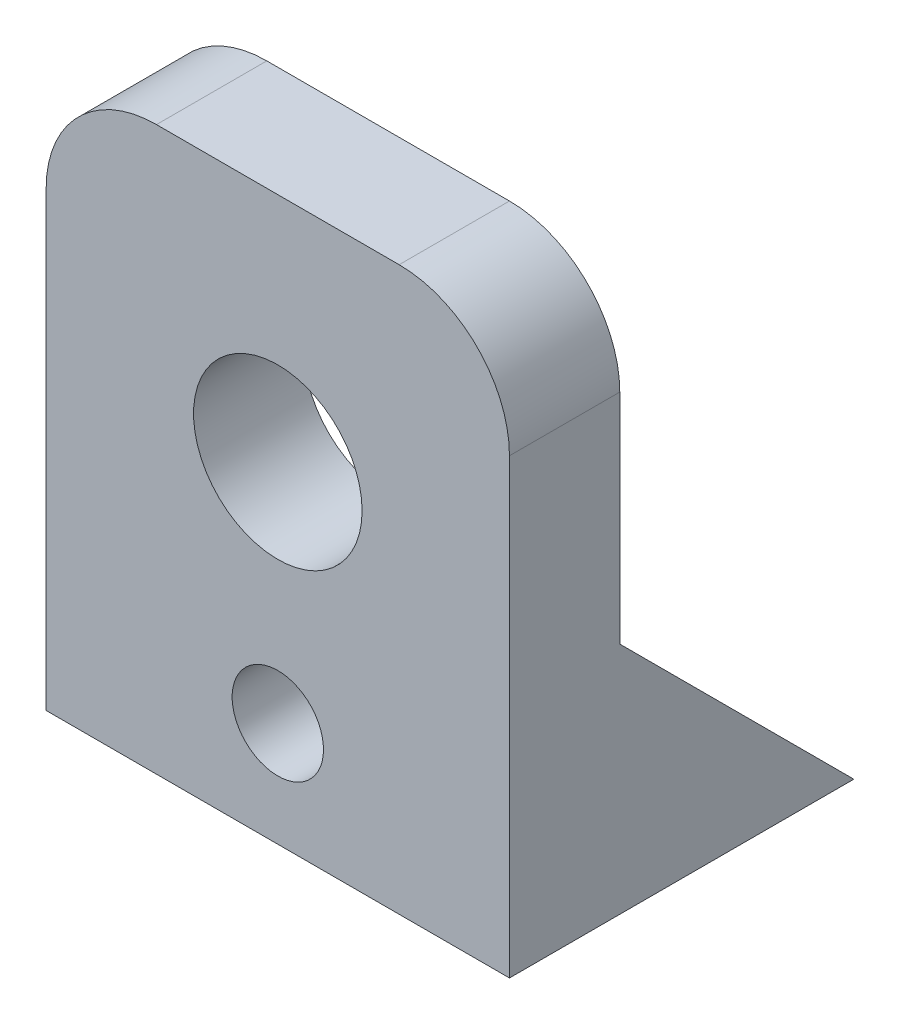
SolidWorks part; units mm, degrees
ref_plane "Front Plane" through (0, 0, 0) normal (0, 0, 1) x (1, 0, 0)
ref_plane "Top Plane" through (0, 0, 0) normal (0, 1, 0) x (1, 0, 0)
ref_plane "Right Plane" through (0, 0, 0) normal (1, 0, 0) x (0, 0, -1)
sketch "Sketch1" plane through (0, 0, 0) normal (0, 0, 1) x (1, 0, 0)
  line L0 (-89.4449, -20.5193) -> (2.5551, -20.5193) construction
  line L2 (-39.4449, 30.4807) -> (-39.4449, -10.5193) construction
  line L3 (2.5551, -20.5193) -> (2.5551, 30.4807) construction
  line L4 (2.5551, 30.4807) -> (-39.4449, 30.4807) construction
  line L8 (-7.4449, 30.4807) -> (-29.4449, 30.4807)
  line L9 (-39.4449, 20.4807) -> (-39.4449, -20.5193)
  line L10 (-39.4449, -20.5193) -> (2.5551, -20.5193)
  line L11 (2.5551, -20.5193) -> (2.5551, 20.4807)
  circle A0 centre (-18.4449, 9.4807) radius 7.64
  circle A1 centre (-18.4449, -11.0193) radius 4.14
  arc A2 (2.5551, 20.4807) -> (-7.4449, 30.4807) centre (-7.4449, 20.4807) ccw
  arc A3 (-39.4449, 20.4807) -> (-29.4449, 30.4807) centre (-29.4449, 20.4807) cw
  dimension "D2" = 10
  dimension "D1" = 8.28
  dimension "D3" = 15.28
extrude "Boss-Extrude1" add sketch "Sketch1" against normal blind 10
sketch "Sketch2" plane through (2.5551, 0, 0) normal (1, 0, 0) x (0, 0, -1)
  line L0 (10, 0.6982) -> (31.2176, -20.5193)
  line L1 (10, -20.5193) -> (10, 20.4807) construction
  line L2 (31.2176, -20.5193) -> (10, -20.5193)
  line L3 (10, -20.5193) -> (10, 0.6982)
  line L4 (10, -20.5193) -> (0, -20.5193) construction
  point P6 (0, 0)
  point P9 (31.2176, -20.5193)
  dimension "D1" = 45
extrude "Boss-Extrude2" add sketch "Sketch2" against normal blind 10 contours L0 L2 L3
